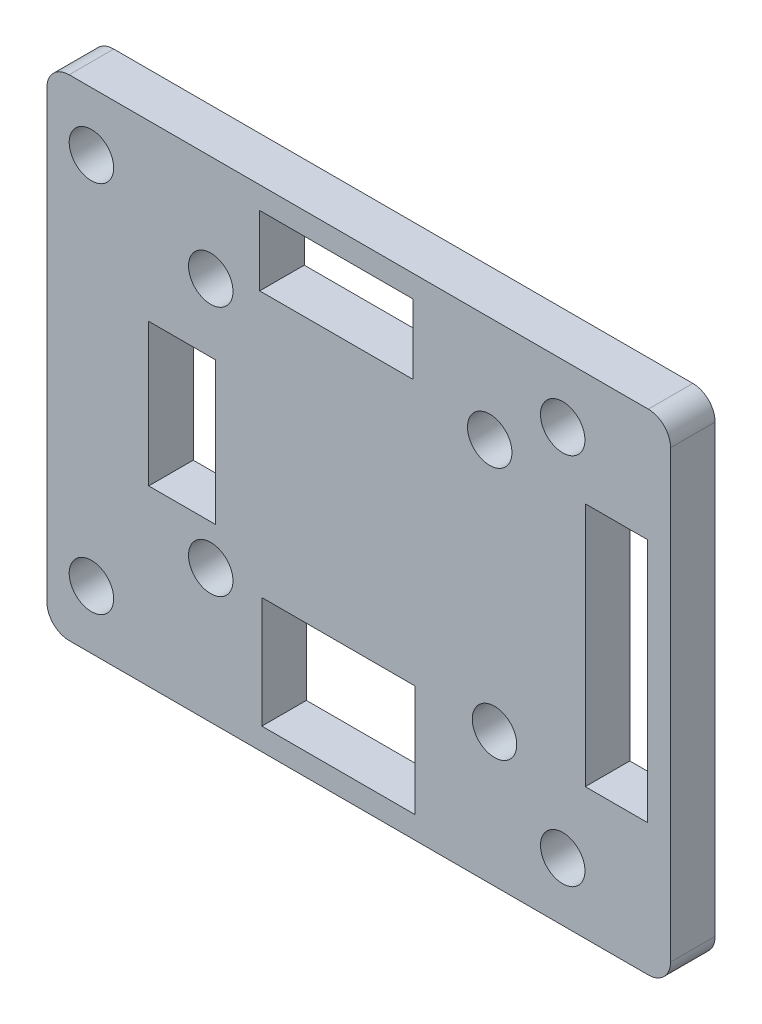
SolidWorks part; units mm, degrees
ref_plane "Front Plane" through (0, 0, 0) normal (0, 0, 1) x (1, 0, 0)
ref_plane "Top Plane" through (0, 0, 0) normal (0, 1, 0) x (1, 0, 0)
ref_plane "Right Plane" through (0, 0, 0) normal (1, 0, 0) x (0, 0, -1)
sketch "Sketch1" plane through (0, 0, 0) normal (0, 0, 1) x (1, 0, 0)
  line L0 (4.7513, 28.3865) -> (4.7779, 28.3865) construction
  line L1 (0, 0) -> (35.56, 0)
  line L2 (0, 0) -> (0, 27.94)
  line L3 (0, 27.94) -> (35.56, 27.94)
  line L4 (35.56, 0) -> (35.56, 27.94)
  line L5 (30.6975, 21.4717) -> (30.6975, 7.5017)
  line L6 (12.2564, 7.62) -> (18.1051, 7.62) construction
  line L7 (20.9943, 7.62) -> (18.1051, 7.62) construction
  line L8 (12.1361, 26.67) -> (12.1361, 22.7012)
  line L9 (12.1361, 22.7012) -> (20.8673, 22.7012)
  line L10 (9.6159, 18.034) -> (9.6159, 9.906)
  line L11 (4.7513, 18.8615) -> (4.7178, 18.8615) construction
  line L12 (1.2725, 25.8762) -> (6.3674, 25.8762) construction
  line L13 (1.2725, 25.8762) -> (1.2725, 22.0236) construction
  line L14 (30.6781, 0.8222) -> (30.6781, 4.2954) construction
  line L15 (30.6781, 2.0638) -> (27.0996, 2.0638) construction
  line L16 (30.6975, 21.4717) -> (34.2535, 21.4717)
  line L17 (5.8059, 18.034) -> (9.6159, 18.034)
  line L18 (9.6159, 9.906) -> (5.8059, 9.906)
  line L19 (20.9943, 7.62) -> (20.9943, 1.27) construction
  line L20 (12.2564, 1.27) -> (12.2564, 7.62) construction
  line L21 (20.8673, 26.67) -> (20.8673, 22.7012)
  line L22 (12.1361, 26.67) -> (20.8673, 26.67)
  line L23 (34.2535, 21.4717) -> (34.2535, 7.5017)
  line L24 (34.2535, 7.5017) -> (30.6975, 7.5017)
  line L25 (12.2564, 1.27) -> (20.9943, 1.27) construction
  line L26 (5.8059, 9.906) -> (5.8059, 18.034)
  line L27 (2.9733, 13.97) -> (36.5013, 13.97) construction
  line L28 (5.8059, 13.97) -> (9.6159, 13.97) construction
  line L29 (0, 13.97) -> (35.56, 13.97) construction
  line L31 (12.2564, 7.62) -> (20.9943, 7.62)
  line L32 (12.2564, 7.62) -> (12.2564, 1.27)
  line L33 (12.2564, 1.27) -> (20.9943, 1.27)
  line L34 (20.9943, 7.62) -> (20.9943, 1.27)
  circle A0 centre (25.5223, 7.62) radius 1.2675 construction
  circle A1 centre (29.4106, 3.3313) radius 1.2675 construction
  circle A2 centre (2.54, 24.6087) radius 1.2675
  circle A3 centre (25.2488, 21.9075) radius 1.2675
  circle A4 centre (9.3421, 7.62) radius 1.2675 construction
  circle A5 centre (9.3421, 21.9075) radius 1.2675
  circle A6 centre (29.4106, 24.6087) radius 1.2675
  circle A7 centre (2.54, 3.3313) radius 1.2675 construction
  circle A8 centre (25.5223, 7.62) radius 1.2675
  circle A9 centre (9.3421, 7.62) radius 1.2675
  circle A10 centre (2.54, 3.3313) radius 1.2675
  circle A11 centre (29.4106, 3.3313) radius 1.2675
  dimension "D10" = 2.535
  dimension "D24" = 5.1752
  dimension "D1" = 35.56
  dimension "D3" = 8.128
  dimension "D4" = 3.9688
  dimension "D5" = 8.7379
  dimension "D6" = 6.35
  dimension "D7" = 25.4
  dimension "D8" = 3.556
  dimension "D9" = 13.97
  dimension "D11" = 3.81
  dimension "D12" = 6.8021
  dimension "D13" = 4.1617
  dimension "D14" = 8.5432
  dimension "D15" = 9.5961
  dimension "D16" = 2.0613
  dimension "D17" = 2.54
  dimension "D18" = 8.7313
  dimension "D19" = 8.7312
  dimension "D20" = 2.5201
  dimension "D21" = 5.4487
  dimension "D22" = 3.137
  dimension "D23" = 0.7937
  dimension "D25" = 0.7937
  dimension "D26" = 2.286
  dimension "D27" = 4.2887
  dimension "D28" = 27.94
  dimension "D29" = 4.528
extrude "Boss-Extrude1" add sketch "Sketch1" along normal blind 2.54
fillet "Fillet1" radius 1.27 4 edges at (35.56, 27.94, 1.27) (35.56, 0, 1.27) (0, 0, 1.27) (0, 27.94, 1.27)
